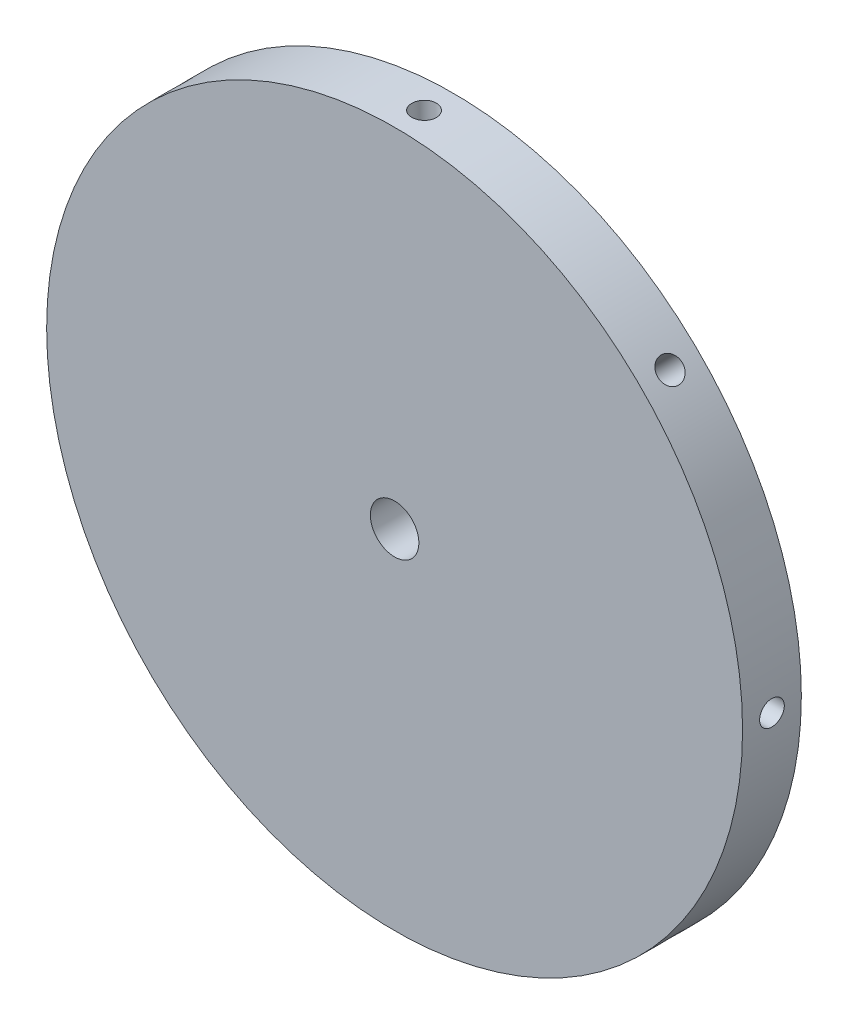
SolidWorks part; units mm, degrees
material "Delrin 2700 NC010, Düşük Viskozite Asetal Kopolimer (SS)"
ref_plane "Ön Düzlem" through (0, 0, 0) normal (0, 0, 1) x (1, 0, 0)
ref_plane "Üst Düzlem" through (0, 0, 0) normal (0, 1, 0) x (1, 0, 0)
ref_plane "Sağ Düzlem" through (0, 0, 0) normal (1, 0, 0) x (0, 0, -1)
sketch "Çizim1" plane through (0, 0, 0) normal (0, 0, 1) x (1, 0, 0)
  circle A0 centre (0, 0) radius 59.2
extrude "Yükseklik-Ekstrüzyon1" add sketch "Çizim1" along normal blind 10
ref_plane "Düzlem1" through (62, 0, 0) normal (1, 0, 0) x (0, 0, -1)
sketch "Çizim2" plane through (62, 0, 0) normal (1, 0, 0) x (0, 0, -1)
  line L0 (-10, 0) -> (-5, 0)
  line L1 (-10, 59.2) -> (-10, -59.2) construction
  circle A0 centre (-5, 0) radius 3
sketch "Çizim5" plane through (62, 0, 0) normal (1, 0, 0) x (0, 0, -1)
  point P0 (-5, 0)
sketch "Çizim9" plane through (62, 0, 0) normal (1, 0, 0) x (0, 0, -1)
  point P0 (-5, 0)
hole_wizard "M4x0.7 Helisarmal İçin Dişli Delik1" positions "Çizim9" profile "Çizim10" tap size "M4x0.7" standard "Helicoil® Metric"
sketch "Çizim10" plane through (62, 0, 5) normal (0, 1, 0) x (0, 0, -1)
  line L0 (0, 0) -> (0, 17.2618)
  line L1 (0, 17.2618) -> (2.1, 16)
  line L2 (2.1, 16) -> (2.1, 0)
  line L5 (2.1, 0) -> (0, 0)
  line L10 (0, 17.2618) -> (-2.1, 16) construction
  line L11 (0, -6.35) -> (0, 107.95) construction
  dimension "Tap Drill Dia." = 4.2
  dimension "Tap Drill Depth" = 16
  dimension "Drill Angle" = 118
pattern_circular "Dairesel Kaplama1" count 8 every 45 about axis through (0, 0, 10) along (0, 0, -1) of "M4x0.7 Helisarmal İçin Dişli Delik1"
sketch "Çizim13" plane through (0, 0, 0) normal (0, 0, -1) x (-1, 0, 0)
  circle A0 centre (0, 0) radius 14.9576
  point P0 (0, 0)
hole_wizard "M8 Helisarmal için Zıvana matkabı2" positions "Çizim13" profile "Çizim14" hole size "M8x1.0" standard "ANSI Metric" end condition through all
sketch "Çizim14" plane through (0, 0, 0) normal (1, 0, 0) x (0, 1, 0)
  line L0 (0, 0) -> (0, 10)
  line L1 (0, 10) -> (4.125, 10)
  line L2 (4.125, 10) -> (4.125, 0)
  line L5 (4.125, 0) -> (0, 0)
  line L11 (0, -6.35) -> (0, 107.95) construction
  dimension "Thru Hole Dia." = 8.25
  dimension "Thru Hole Depth" = 10
sketch "Çizim15" plane through (0, 0, 0) normal (0, 0, -1) x (-1, 0, 0)
